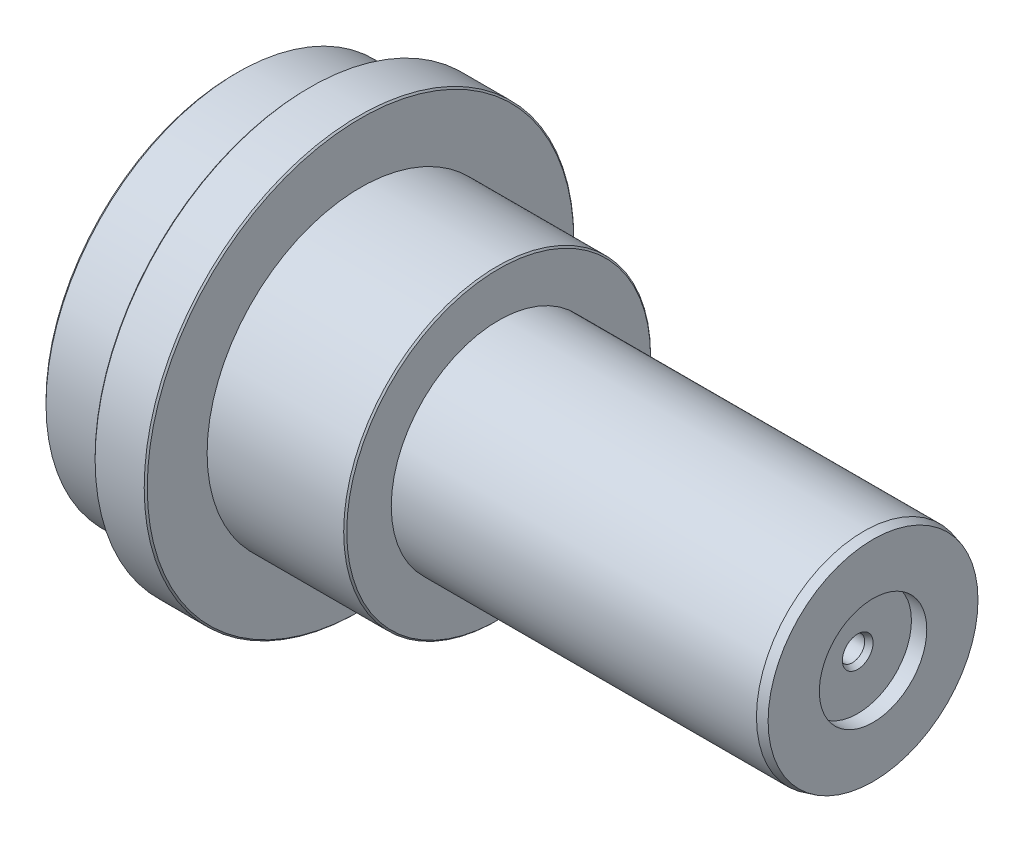
SolidWorks part; units mm, degrees
ref_plane "前基準面" through (0, 0, 0) normal (0, 0, 1) x (1, 0, 0)
ref_plane "上基準面" through (0, 0, 0) normal (0, 1, 0) x (1, 0, 0)
ref_plane "右基準面" through (0, 0, 0) normal (1, 0, 0) x (0, 0, -1)
ref_plane "平面1" through (0, 0, 0) normal (0, 0, -1) x (-1, 0, 0)
sketch "草圖1" plane through (0, 0, 0) normal (0, 0, -1) x (-1, 0, 0)
  line L0 (-41, 70) -> (-41, 0)
  line L1 (-41, 0) -> (-24, 0)
  line L2 (-24, 0) -> (-24, 70)
  line L3 (-24, 70) -> (-41, 70)
  line L4 (-41, 0) -> (-24, 0) construction
revolve "旋轉1" add sketch "草圖1" angle 360 about L4
sketch "草圖2" plane through (24, 0, 0) normal (-1, 0, 0) x (0, 0, 1)
  circle A0 centre (0, 0) radius 62.5
extrude "填料-伸長1" add sketch "草圖2" along normal blind 24
sketch "草圖3" plane through (41, 0, 0) normal (1, 0, 0) x (0, 0, -1)
  circle A0 centre (0, 0) radius 50
extrude "填料-伸長2" add sketch "草圖3" along normal blind 45
sketch "草圖4" plane through (86, 0, 0) normal (1, 0, 0) x (0, 0, -1)
  circle A0 centre (0, 0) radius 35
extrude "填料-伸長3" add sketch "草圖4" along normal blind 122
hole_wizard "鑽孔3" positions "草圖10" profile "草圖9" legacy
sketch "草圖10" plane through (208, 0, 0) normal (1, 0, 0) x (0, 0, -1)
  point P0 (0, 0)
sketch "草圖9" plane through (208, 0, 0) normal (0, 1, 0) x (0, 0, -1)
  line L0 (0, 0) -> (0, 17.4034)
  line L1 (0, 17.4034) -> (4, 15)
  line L2 (4, 15) -> (4, 5)
  line L3 (4, 5) -> (17.5, 5)
  line L4 (17.5, 0) -> (0, 0)
  line L5 (0, -11.3109) -> (0, 121.1557) construction
  line L6 (0, 17.4034) -> (-4, 15) construction
  line L7 (17.5, 5) -> (17.5, 0)
  dimension "直徑" = 8
  dimension "深度" = 15
  dimension "柱孔直徑1" = 35
  dimension "柱孔深度1" = 5
  dimension "導頭角度" = 118
hole_wizard "鑽孔5" positions "草圖14" profile "草圖13" legacy
sketch "草圖14" plane through (0, 0, 0) normal (-1, 0, 0) x (0, 0, 1)
  point P0 (0, 0)
sketch "草圖13" plane through (0, 0, 0) normal (0, 1, 0) x (0, 0, 1)
  line L0 (0, 0) -> (0, 14.4034)
  line L1 (0, 14.4034) -> (4, 12)
  line L2 (4, 12) -> (4, 2)
  line L3 (4, 2) -> (12.5, 2)
  line L4 (12.5, 0) -> (0, 0)
  line L5 (0, -11.3109) -> (0, 121.1557) construction
  line L6 (0, 14.4034) -> (-4, 12) construction
  line L7 (12.5, 2) -> (12.5, 0)
  dimension "直徑" = 8
  dimension "深度" = 12
  dimension "柱孔直徑1" = 25
  dimension "柱孔深度1" = 2
  dimension "導頭角度" = 118
chamfer "導角2" distance 0.8038 angle 75 1 edges at (208, 0, -35)
chamfer "導角3" distance 1 angle 60 2 edges at (2, 0, 4) (203, 0, -4)
chamfer "導角4" distance 0.5 angle 45 3 edges at (41, 0, 70) (86, 0, -50) (24, 0, 70)
chamfer "導角5" distance 1 angle 45 1 edges at (0, 0, 62.5)
